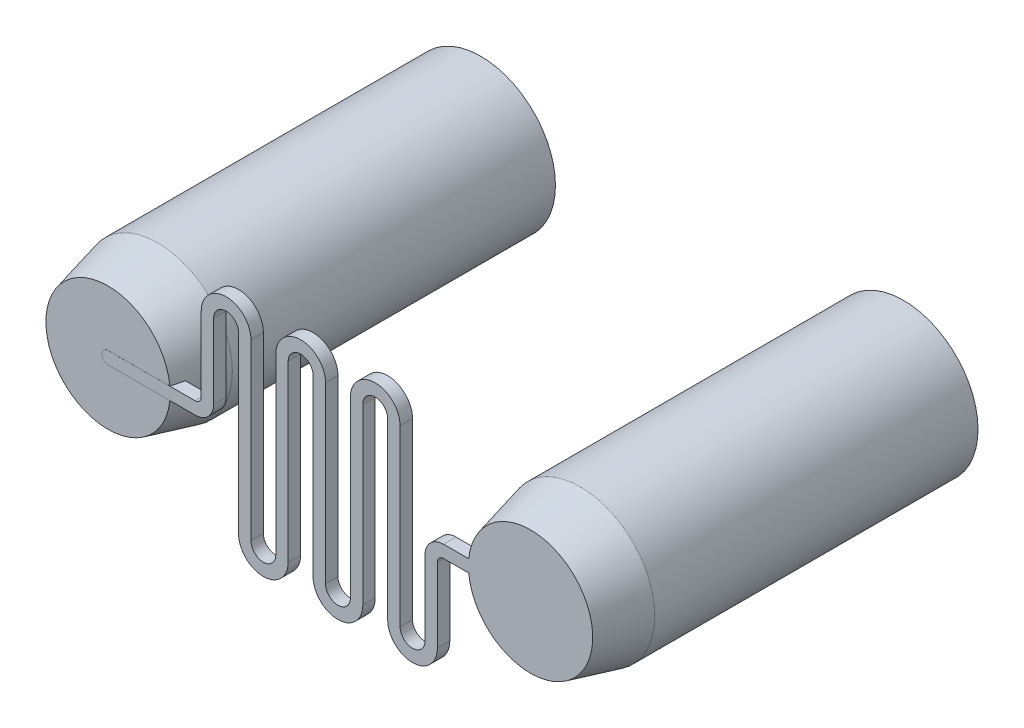
SolidWorks part; units mm, degrees
ref_plane "Front Plane" through (0, 0, 0) normal (0, 0, 1) x (1, 0, 0)
ref_plane "Top Plane" through (0, 0, 0) normal (0, 1, 0) x (1, 0, 0)
ref_plane "Right Plane" through (0, 0, 0) normal (1, 0, 0) x (0, 0, -1)
sketch "Sketch2" plane through (0, 0, 0) normal (0, 0, 1) x (1, 0, 0)
  line L3 (-20.5, -0.5) -> (-13.5, -0.5)
  line L6 (-12, 1) -> (-12, 7)
  line L9 (-10, 7) -> (-10, 0)
  line L12 (-10, 0) -> (-10, -7)
  line L15 (-6, -7) -> (-6, 0)
  line L18 (-6, 0) -> (-6, 7)
  line L21 (-4, 7) -> (-4, 0)
  line L22 (-4, 0) -> (-4, -7)
  line L23 (0, -7) -> (0, 0)
  line L24 (0, 0) -> (0, 7)
  line L25 (2, 7) -> (2, 0)
  line L26 (2, 0) -> (2, -7)
  line L27 (6, -7) -> (6, -1)
  line L28 (6.5, -0.5) -> (13.5, -0.5)
  line L29 (-20.5, 0.5) -> (-13.5, 0.5)
  line L30 (-13, 1) -> (-13, 7)
  line L31 (-9, 7) -> (-9, 0)
  line L32 (-9, 0) -> (-9, -7)
  line L33 (-7, -7) -> (-7, 0)
  line L34 (-7, 0) -> (-7, 7)
  line L35 (-3, 7) -> (-3, 0)
  line L36 (-3, 0) -> (-3, -7)
  line L37 (-1, -7) -> (-1, 0)
  line L38 (-1, 0) -> (-1, 7)
  line L39 (3, 7) -> (3, 0)
  line L40 (3, 0) -> (3, -7)
  line L41 (5, -7) -> (5, -1)
  line L42 (6.5, 0.5) -> (13.5, 0.5)
  arc A0 (-20.5, 0.5) -> (-20.5, -0.5) centre (-20.5, 0) ccw
  arc A1 (13.5, -0.5) -> (13.5, 0.5) centre (13.5, 0) ccw
  arc A8 (-12, 1) -> (-13.5, -0.5) centre (-13.5, 1) cw
  arc A9 (-12, 7) -> (-10, 7) centre (-11, 7) cw
  arc A10 (-10, -7) -> (-6, -7) centre (-8, -7) ccw
  arc A11 (-6, 7) -> (-4, 7) centre (-5, 7) cw
  arc A12 (-4, -7) -> (0, -7) centre (-2, -7) ccw
  arc A13 (0, 7) -> (2, 7) centre (1, 7) cw
  arc A14 (2, -7) -> (6, -7) centre (4, -7) ccw
  arc A15 (6, -1) -> (6.5, -0.5) centre (6.5, -1) cw
  arc A16 (-13, 1) -> (-13.5, 0.5) centre (-13.5, 1) cw
  arc A17 (-13, 7) -> (-9, 7) centre (-11, 7) cw
  arc A18 (-9, -7) -> (-7, -7) centre (-8, -7) ccw
  arc A19 (-7, 7) -> (-3, 7) centre (-5, 7) cw
  arc A20 (-3, -7) -> (-1, -7) centre (-2, -7) ccw
  arc A21 (-1, 7) -> (3, 7) centre (1, 7) cw
  arc A22 (3, -7) -> (5, -7) centre (4, -7) ccw
  arc A23 (5, -1) -> (6.5, 0.5) centre (6.5, -1) cw
  point P4 (0, 0)
  point P32 (5.5, 0)
  point P35 (-12.5, 0)
extrude "Boss-Extrude1" add sketch "Sketch2" along normal blind 1
ref_plane "Plane1" through (0, 0, 0) normal (0, 1, 0) x (1, 0, 0)
sketch "Sketch3" plane through (0, 0, 0) normal (0, 1, 0) x (1, 0, 0)
  line L0 (-20.5, -0.9984) -> (-25.5, -0.9984)
  line L1 (-20.5, -1) -> (-20.5, 0) construction
  line L3 (-20.5, -0.9984) -> (-20.5, 29.0016)
  line L4 (-20.5, 29.0016) -> (-26.5, 29.0016)
  line L5 (-26.5, 29.0016) -> (-26.5, 3.0016)
  line L6 (-26.5, 3.0016) -> (-25.5, -0.9984)
  dimension "D1" = 5
  dimension "D3" = 30
  dimension "D4" = 6
revolve "Revolve1" add sketch "Sketch3" angle 360 about L3
ref_plane "Plane2" through (0, 0, 0) normal (0, 1, 0) x (1, 0, 0)
sketch "Sketch4" plane through (0, 0, 0) normal (0, 1, 0) x (1, 0, 0)
  line L0 (13.5, -1) -> (18.5, -1)
  line L2 (13.5, -1) -> (13.5, 29)
  line L3 (13.5, 29) -> (19.5, 29)
  line L4 (19.5, 29) -> (19.5, 3)
  line L5 (19.5, 3) -> (18.5, -1)
  dimension "D1" = 5
  dimension "D3" = 30
  dimension "D4" = 6
revolve "Revolve2" add sketch "Sketch4" angle 360 about L2
sketch "Sketch5" plane through (0, 0, -29.0016) normal (0, 0, -1) x (-1, 0, 0)
  circle A0 centre (20.5, 0) radius 5
  circle A1 centre (-13.5, 0) radius 5
  dimension "D1" = 10
  dimension "D2" = 10
extrude "Cut-Extrude1" cut sketch "Sketch5" against normal blind 26
